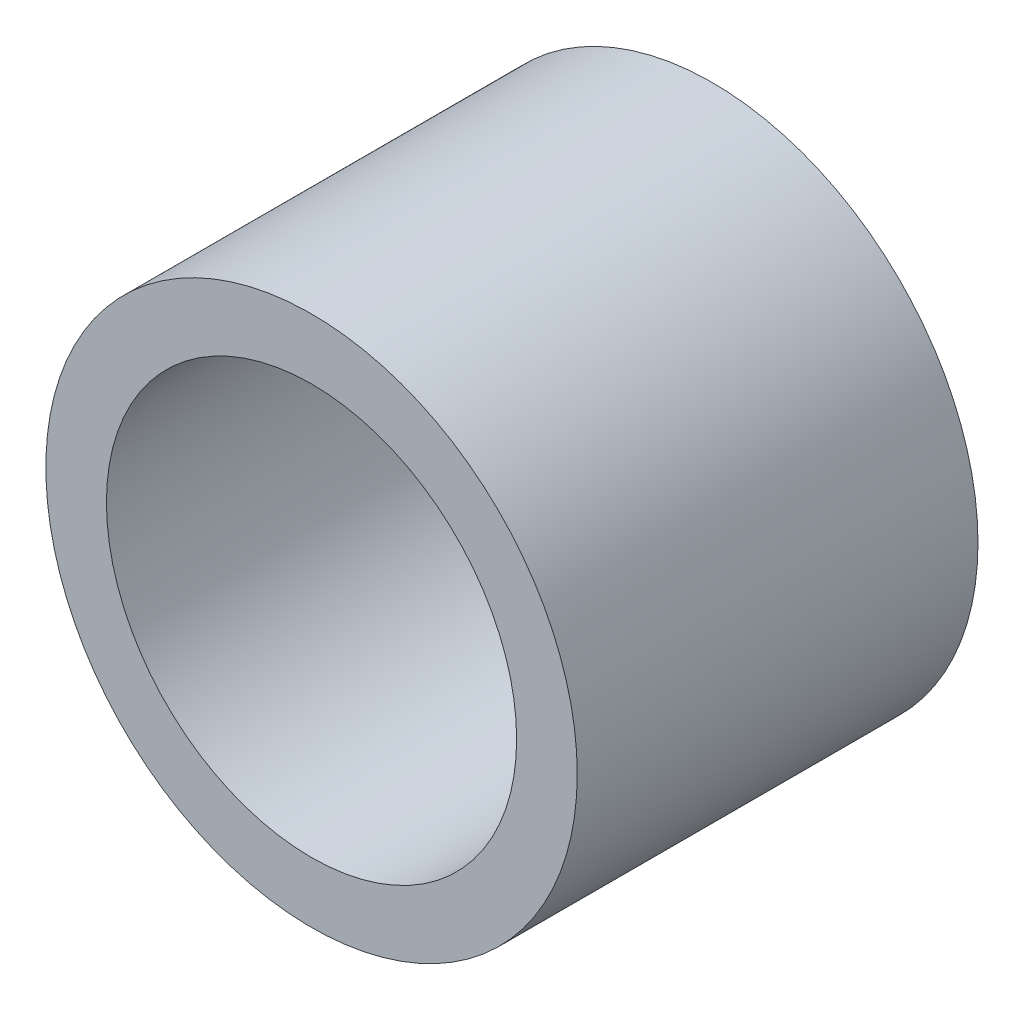
SolidWorks part; units mm, degrees
ref_plane "Front Plane" through (0, 0, 0) normal (0, 0, 1) x (1, 0, 0)
ref_plane "Top Plane" through (0, 0, 0) normal (0, 1, 0) x (1, 0, 0)
ref_plane "Right Plane" through (0, 0, 0) normal (1, 0, 0) x (0, 0, -1)
sketch "Sketch1" plane through (0, 0, 0) normal (0, 1, 0) x (1, 0, 0)
  line L0 (0, 0) -> (0, 28.9895) construction
  line L1 (0, 0) -> (13, 0)
  line L2 (13, 0) -> (13, 23.7817)
  line L3 (0, 28.9895) -> (0, 29.4)
  line L4 (13, 0) -> (16.8412, 0)
  line L5 (16.8412, 0) -> (16.8412, 25.4)
  spline S0 degree 2 poles (0, 28.9895) (6.524, 26.4456) (13, 23.7817) knots 0 0 0 1 1 1
  spline S1 degree 2 poles (0, 29.4) (8.6789, 28.5547) (16.8412, 25.4) knots 0 0 0 1 1 1
  point P10 (0, 0)
revolve "Revolve2" add sketch "Sketch1" angle 360 about L0
